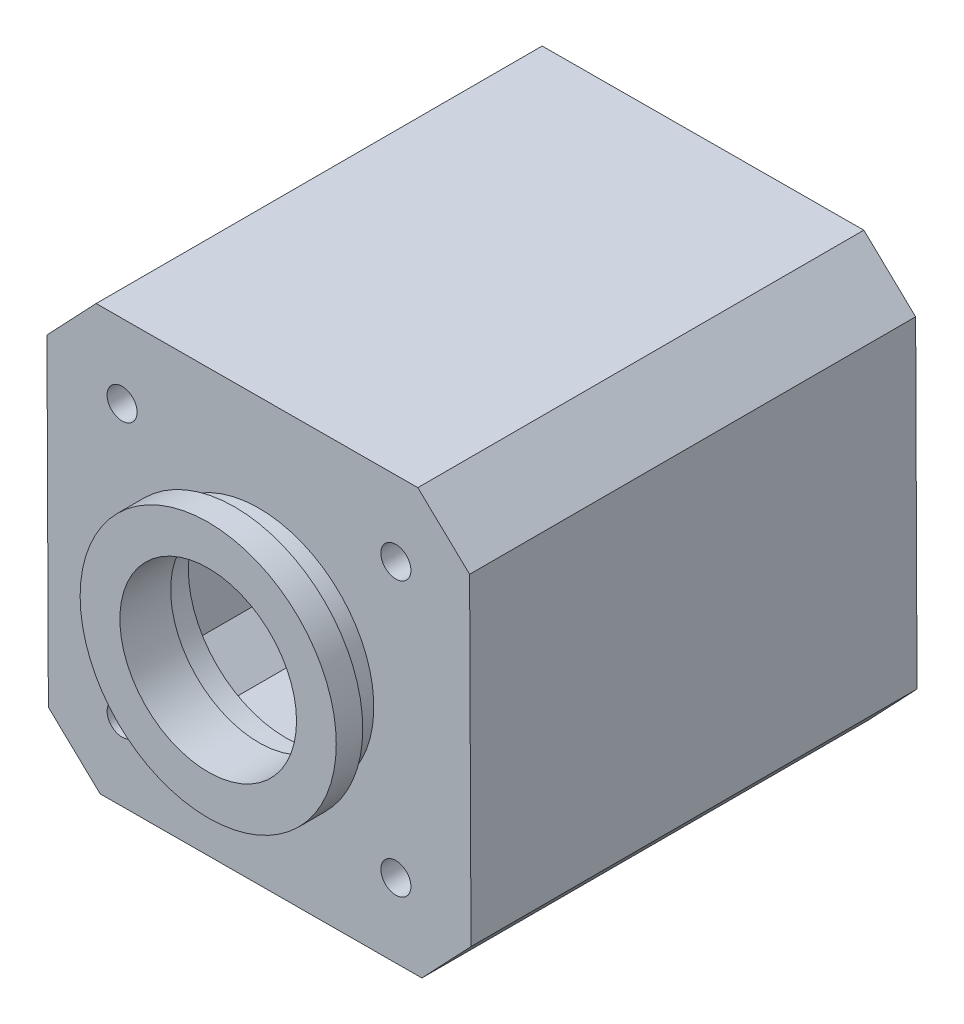
SolidWorks part; units mm, degrees
ref_plane "Alzado" through (0, 0, 0) normal (0, 0, 1) x (1, 0, 0)
ref_plane "Planta" through (0, 0, 0) normal (0, 1, 0) x (1, 0, 0)
ref_plane "Vista lateral" through (0, 0, 0) normal (1, 0, 0) x (0, 0, -1)
sketch "Croquis1" plane through (0, 0, 0) normal (0, 0, 1) x (1, 0, 0)
  line L16 (-20.9122, -17.5447) -> (-21.0586, 16.3947)
  line L17 (-21.0586, 16.3947) -> (-17.2051, 20.4553)
  line L18 (-17.2051, 20.4553) -> (16.7343, 20.6018)
  line L19 (16.7343, 20.6018) -> (20.7949, 16.7482)
  line L20 (20.7949, 16.7482) -> (20.9414, -17.1911)
  line L21 (20.9414, -17.1911) -> (17.0878, -21.2518)
  line L22 (17.0878, -21.2518) -> (-16.8515, -21.3982)
  line L23 (-16.8515, -21.3982) -> (-20.9122, -17.5447)
  circle A6 centre (-15.5586, 15.1018) radius 1.7
  circle A7 centre (15.4414, 15.1018) radius 1.7
  circle A8 centre (15.4414, -15.8982) radius 1.7
  circle A9 centre (-15.5586, -15.8982) radius 1.7
extrude "Saliente-Extruir1" add sketch "Croquis1" along normal blind 3
sketch "Croquis17" plane through (0, 0, 3) normal (0, 0, 1) x (1, 0, 0)
  line L0 (-20.9854, -0.575) -> (20.8682, -0.2215) construction
  line L1 (-21.0586, 16.3947) -> (-20.9122, -17.5447) construction
  line L2 (20.9414, -17.1911) -> (20.7949, 16.7482) construction
  circle A1 centre (-0.0586, -0.3982) radius 11
  dimension "D2" = 22
extrude "Cortar-Extruir7" cut sketch "Croquis17" against normal blind 30
sketch "Croquis19" plane through (0, 0, 3) normal (0, 0, 1) x (1, 0, 0)
  circle A1 centre (-0.0586, -0.3982) radius 13
  dimension "D1" = 26
extrude "Saliente-Extruir3" add sketch "Croquis19" along normal blind 7.25
sketch "Croquis20" plane through (0, 0, 10.25) normal (0, 0, 1) x (1, 0, 0)
  circle A1 centre (-0.0586, -0.3982) radius 10
  dimension "D1" = 20
extrude "Cortar-Extruir8" cut sketch "Croquis20" against normal blind 14
sketch "Croquis22" plane through (0, 0, 10.25) normal (0, 0, 1) x (1, 0, 0)
  circle A1 centre (-0.0586, -0.3982) radius 13
  circle A2 centre (-0.0586, -0.3982) radius 13
  dimension "D1" = 0
extrude "Cortar-Extruir9" cut sketch "Croquis22" against normal blind 1.5
sketch "Croquis23" plane through (0, 0, 8.75) normal (0, 0, 1) x (1, 0, 0)
  circle A2 centre (-0.0586, -0.3982) radius 14.5
  circle A3 centre (-0.0586, -0.3982) radius 13 construction
  circle A4 centre (-0.0586, -0.3982) radius 13
  dimension "D1" = 29
extrude "Saliente-Extruir4" add sketch "Croquis23" against normal blind 3
sketch "Croquis25" plane through (0, 0, 3) normal (0, 0, 1) x (1, 0, 0)
  line L0 (-24.0638, 17.5861) -> (-18.4992, 23.4498)
  line L8 (-20.9122, -17.5447) -> (-16.8515, -21.3982) construction
  line L9 (-16.8515, -21.3982) -> (17.0878, -21.2518) construction
  line L10 (17.0878, -21.2518) -> (20.9414, -17.1911) construction
  line L11 (20.9414, -17.1911) -> (20.7949, 16.7482) construction
  line L12 (20.7949, 16.7482) -> (16.7343, 20.6018) construction
  line L13 (16.7343, 20.6018) -> (-17.2051, 20.4553) construction
  line L14 (-17.2051, 20.4553) -> (-21.0586, 16.3947) construction
  line L15 (-21.0586, 16.3947) -> (-20.9122, -17.5447) construction
  line L16 (23.7894, 18.0424) -> (17.9257, 23.6069)
  line L17 (23.9466, -18.3826) -> (23.7894, 18.0424)
  line L18 (18.382, -24.2462) -> (23.9466, -18.3826)
  line L19 (-18.043, -24.4034) -> (18.382, -24.2462)
  line L20 (-23.9066, -18.8388) -> (-18.043, -24.4034)
  line L21 (-24.0638, 17.5861) -> (-23.9066, -18.8388)
  line L22 (-18.4992, 23.4498) -> (-24.0638, 17.5861)
  line L23 (17.9257, 23.6069) -> (-18.4992, 23.4498)
  line L24 (23.7894, 18.0424) -> (17.9257, 23.6069)
  line L25 (23.9466, -18.3826) -> (23.7894, 18.0424)
  line L26 (18.382, -24.2462) -> (23.9466, -18.3826)
  line L27 (-18.043, -24.4034) -> (18.382, -24.2462)
  line L28 (-23.9066, -18.8388) -> (-18.043, -24.4034)
  line L29 (-24.0638, 17.5861) -> (-23.9066, -18.8388)
  line L31 (17.9257, 23.6069) -> (-18.4992, 23.4498)
  line L32 (-20.9122, -17.5447) -> (-16.8515, -21.3982)
  line L33 (-16.8515, -21.3982) -> (17.0878, -21.2518)
  line L34 (17.0878, -21.2518) -> (20.9414, -17.1911)
  line L35 (20.9414, -17.1911) -> (20.7949, 16.7482)
  line L36 (20.7949, 16.7482) -> (16.7343, 20.6018)
  line L37 (16.7343, 20.6018) -> (-17.2051, 20.4553)
  line L38 (-17.2051, 20.4553) -> (-21.0586, 16.3947)
  line L39 (-21.0586, 16.3947) -> (-20.9122, -17.5447)
  dimension "D1" = 3
extrude "Saliente-Extruir6" add sketch "Croquis25" against normal blind 50.5
